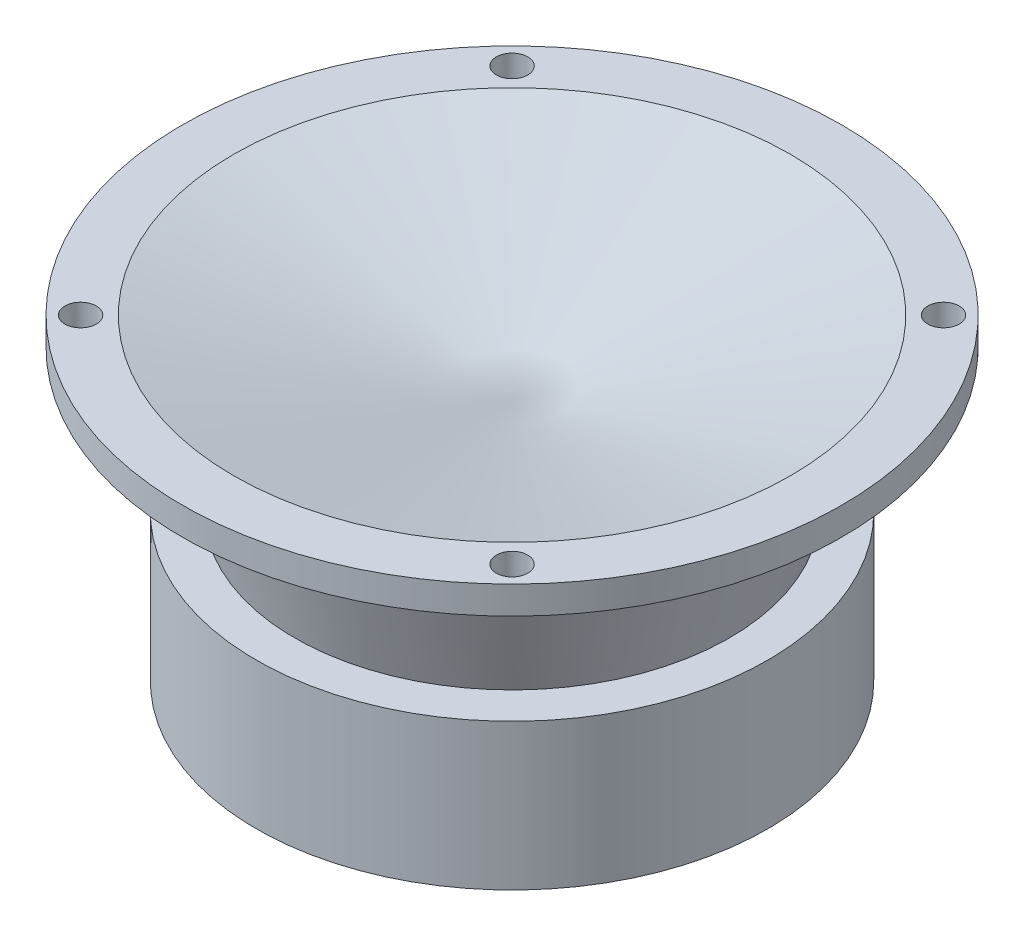
SolidWorks part; units mm, degrees
ref_plane "Front Plane" through (0, 0, 0) normal (0, 0, 1) x (1, 0, 0)
ref_plane "Top Plane" through (0, 0, 0) normal (0, 1, 0) x (1, 0, 0)
ref_plane "Right Plane" through (0, 0, 0) normal (1, 0, 0) x (0, 0, -1)
sketch "Sketch1" plane through (0, 0, 0) normal (0, 0, 1) x (1, 0, 0)
  line L0 (0, 0) -> (0, 43.4) construction
  line L1 (0, 33.1911) -> (38.1, 43.4)
  line L2 (38.1, 43.4) -> (45.1, 43.4)
  line L3 (45.1, 43.4) -> (45.1, 39.6)
  line L4 (45.1, 39.6) -> (35, 39.6)
  line L5 (35, 39.6) -> (29.7482, 20)
  line L6 (29.7482, 20) -> (35, 20)
  line L7 (35, 20) -> (35, 0)
  line L8 (35, 0) -> (0, 0)
  line L9 (0, 0) -> (0, 33.1911)
  dimension "D1" = 90.2
  dimension "D2" = 76.2
  dimension "D3" = 3.8
  dimension "D4" = 70
  dimension "D5" = 15
  dimension "D6" = 20
  dimension "D7" = 75
  dimension "D8" = 43.4
revolve "Revolve1" add sketch "Sketch1" angle 360 about L0
sketch "Sketch4" plane through (0, 39.6, 0) normal (0, -1, 0) x (1, 0, 0)
  line L1 (-31.434, -12) -> (-38, -12)
  line L2 (-31.434, -12) -> (-31.434, 12)
  line L3 (-31.434, 12) -> (-38, 12)
  line L4 (-38, -12) -> (-38, 12)
  line L5 (-34.717, 12) -> (-34.717, -12) construction
  line L6 (-31.434, 0) -> (-38, 0) construction
  point P0 (-34.717, 0)
  dimension "D1" = 24
  dimension "D2" = 38
extrude "Boss-Extrude1" add sketch "Sketch4" along normal blind 17.5
hole_wizard "Ø4.3 (4.3) Diameter Hole1" positions "Sketch2" profile "Sketch3" hole size "Ø4.3" standard "ANSI Metric" end condition through all
sketch "Sketch2" plane through (0, 43.4, 0) normal (0, 1, 0) x (1, 0, 0)
  line L0 (-29.5217, 29.5217) -> (-29.5217, -29.5217) construction
  line L1 (-29.5217, -29.5217) -> (29.5217, -29.5217) construction
  circle A0 centre (0, 0) radius 41.75
  point P5 (-29.5217, 29.5217)
  point P7 (29.5217, 29.5217)
  point P9 (29.5217, -29.5217)
  point P11 (-29.5217, -29.5217)
  dimension "D1" = 83.5
sketch "Sketch3" plane through (-29.5217, 43.4, 29.5217) normal (1, 0, 0) x (0, 0, 1)
  line L0 (0, 0) -> (0, 43.4)
  line L1 (0, 43.4) -> (2.15, 43.4)
  line L2 (2.15, 43.4) -> (2.15, 0)
  line L5 (2.15, 0) -> (0, 0)
  line L11 (0, -6.35) -> (0, 107.95) construction
  dimension "Thru Hole Dia." = 4.3
  dimension "Thru Hole Depth" = 43.4
sketch "Sketch5" plane through (0, 0, 0) normal (0, -1, 0) x (1, 0, 0)
  circle A0 centre (0, 0) radius 38
